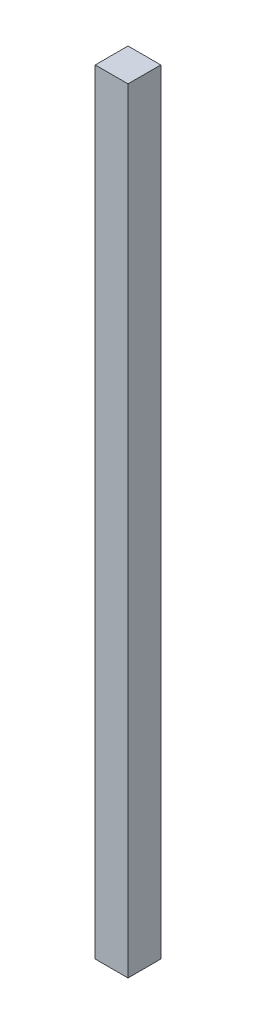
SolidWorks part; units mm, degrees
ref_plane "Front Plane" through (0, 0, 0) normal (0, 0, 1) x (1, 0, 0)
ref_plane "Top Plane" through (0, 0, 0) normal (0, 1, 0) x (1, 0, 0)
ref_plane "Right Plane" through (0, 0, 0) normal (1, 0, 0) x (0, 0, -1)
sketch "Sketch1" plane through (0, 0, 0) normal (0, 1, 0) x (1, 0, 0)
  line L1 (0, 0) -> (25.4, 0)
  line L2 (0, 0) -> (0, 25.4)
  line L3 (0, 25.4) -> (25.4, 25.4)
  line L4 (25.4, 0) -> (25.4, 25.4)
  dimension "D1" = 25.4
extrude "Boss-Extrude1" add sketch "Sketch1" along normal blind 600
